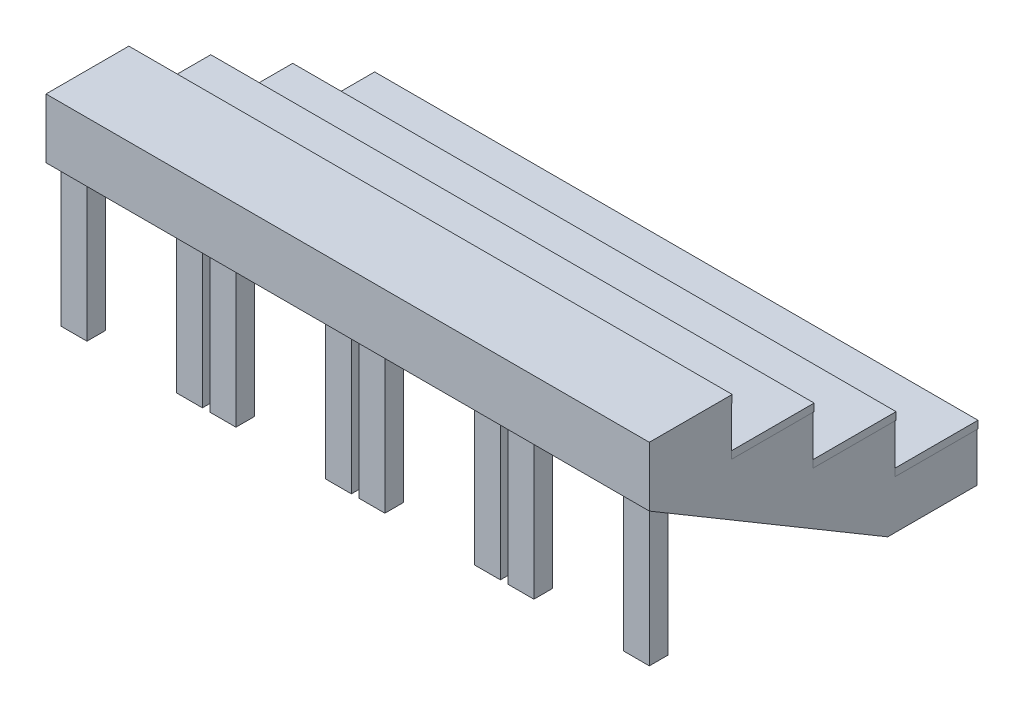
SolidWorks part; units mm, degrees
material "Cedar"
ref_plane "Front" through (0, 0, 0) normal (0, 0, 1) x (1, 0, 0)
ref_plane "Top" through (0, 0, 0) normal (0, 1, 0) x (1, 0, 0)
ref_plane "Right" through (0, 0, 0) normal (1, 0, 0) x (0, 0, -1)
sketch "Sketch1" plane through (0, 0, 0) normal (1, 0, 0) x (0, 0, -1)
  line L0 (0, 0) -> (0, 165.1)
  line L1 (0, 165.1) -> (-279.4, 165.1)
  line L2 (-279.4, 165.1) -> (-279.4, 330.2)
  line L3 (-279.4, 330.2) -> (-558.8, 330.2)
  line L4 (-558.8, 330.2) -> (-558.8, 495.3)
  line L5 (-558.8, 495.3) -> (-838.2, 495.3)
  line L6 (-838.2, 495.3) -> (-838.2, 660.4)
  line L7 (-838.2, 660.4) -> (-1117.6, 660.4)
  line L8 (-1117.6, 660.4) -> (-1117.6, 482.6)
  line L9 (-1117.6, 482.6) -> (-304.8, 0)
  line L10 (-304.8, 0) -> (0, 0)
  dimension "D1" = 165.1
  dimension "D2" = 279.4
  dimension "D3" = 304.8
  dimension "D4" = 177.8
extrude "Boss-Extrude1" add sketch "Sketch1" along normal blind 25.4
pattern_linear "LPattern1" count 5 spacing 508 along (1, 0, 0) of bodies 179
sketch "Sketch2" plane through (2057.4, 0, 0) normal (1, 0, 0) x (0, 0, -1)
  line L1 (-279.4, 165.1) -> (3.175, 165.1)
  line L2 (-279.4, 165.1) -> (-279.4, 190.5)
  line L3 (-279.4, 190.5) -> (3.175, 190.5)
  line L4 (3.175, 165.1) -> (3.175, 190.5)
  line L5 (-558.8, 330.2) -> (-276.225, 330.2)
  line L6 (-558.8, 330.2) -> (-558.8, 355.6)
  line L7 (-558.8, 355.6) -> (-276.225, 355.6)
  line L8 (-276.225, 330.2) -> (-276.225, 355.6)
  line L9 (-838.2, 495.3) -> (-555.625, 495.3)
  line L10 (-838.2, 495.3) -> (-838.2, 520.7)
  line L11 (-838.2, 520.7) -> (-555.625, 520.7)
  line L12 (-555.625, 495.3) -> (-555.625, 520.7)
  line L13 (-1117.6, 660.4) -> (-835.025, 660.4)
  line L14 (-1117.6, 660.4) -> (-1117.6, 685.8)
  line L15 (-1117.6, 685.8) -> (-835.025, 685.8)
  line L16 (-835.025, 660.4) -> (-835.025, 685.8)
  dimension "D1" = 282.575
  dimension "D2" = 25.4
extrude "Boss-Extrude2" add sketch "Sketch2" against normal up to surface (2057.4 mm away) separate body up to face at (0, 344.0545, 535.7091)
sketch "Sketch3" plane through (25.4, 0, 0) normal (1, 0, 0) x (0, 0, -1)
  line L1 (-1117.6, 660.4) -> (-1092.2, 660.4)
  line L2 (-1117.6, 660.4) -> (-1117.6, 482.6)
  line L3 (-1117.6, 482.6) -> (-1092.2, 482.6)
  line L4 (-1092.2, 660.4) -> (-1092.2, 482.6)
  dimension "D1" = 177.8
  dimension "D2" = 25.4
extrude "Boss-Extrude3" add sketch "Sketch3" along normal up to surface (2006.6 mm away)
sketch "Sketch5" plane through (0, 660.4, 0) normal (0, -1, 0) x (1, 0, 0)
  line L1 (25.4, 1092.2) -> (114.3, 1092.2)
  line L2 (25.4, 1092.2) -> (25.4, 1028.7)
  line L3 (25.4, 1028.7) -> (114.3, 1028.7)
  line L4 (114.3, 1092.2) -> (114.3, 1028.7)
  line L5 (508, 1092.2) -> (419.1, 1092.2)
  line L6 (508, 1092.2) -> (508, 1028.7)
  line L7 (508, 1028.7) -> (419.1, 1028.7)
  line L8 (419.1, 1092.2) -> (419.1, 1028.7)
  dimension "D1" = 88.9
  dimension "D2" = 63.5
  dimension "D3" = 88.9
  dimension "D4" = 63.5
extrude "Boss-Extrude4" add sketch "Sketch5" along normal up to surface (660.4 mm away) separate body up to face at (12.7, 0, 152.4)
pattern_linear "LPattern2" count 4 spacing 508 along (1, 0, 0) of bodies 189 190
